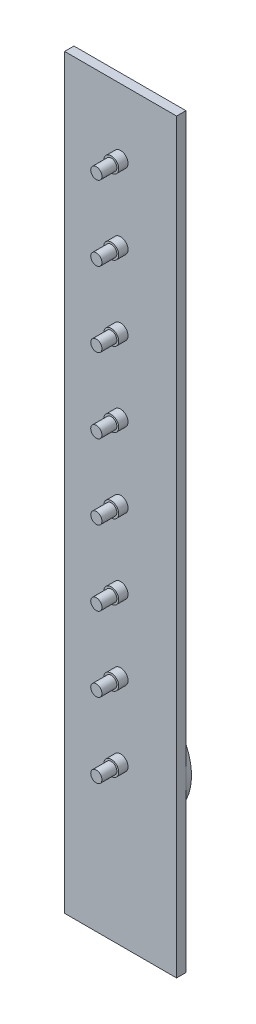
SolidWorks part; units mm, degrees
ref_plane "Спереди" through (0, 0, 0) normal (0, 0, 1) x (1, 0, 0)
ref_plane "Сверху" through (0, 0, 0) normal (0, 1, 0) x (1, 0, 0)
ref_plane "Справа" through (0, 0, 0) normal (1, 0, 0) x (0, 0, -1)
other "Configuration Table"
sketch "Sketch1" plane through (0, 0, 0) normal (0, 0, 1) x (1, 0, 0)
  line L1 (-30, -200) -> (30, -200)
  line L2 (-30, -200) -> (-30, 200)
  line L3 (-30, 200) -> (30, 200)
  line L4 (30, -200) -> (30, 200)
  line L5 (-30, -200) -> (30, 200) construction
  line L6 (-30, 200) -> (30, -200) construction
  point P0 (0, 0)
  dimension "D1" = 60
  dimension "D2" = 400
extrude "Boss-Extrude1" add sketch "Sketch1" along normal blind 5
sketch "Sketch2" plane through (0, 0, 0) normal (0, 0, -1) x (-1, 0, 0)
  line L0 (30, 200) -> (30, -200) construction
  circle A0 centre (0, -110) radius 30
  point P2 (0.2947, -29.9986)
  point P4 (0, 0)
  point P7 (0, -61.8151)
  dimension "D1" = 80
extrude "Boss-Extrude2" add sketch "Sketch2" along normal blind 3
sketch "Sketch3" plane through (0, 0, 5) normal (0, 0, 1) x (1, 0, 0)
  line L0 (0, 186.2824) -> (0, -60.2881) construction
  line L2 (30, 200) -> (-30, 200) construction
  circle A0 centre (0, 165) radius 3
  dimension "D1" = 6
  dimension "D2" = 35
extrude "Boss-Extrude3" add sketch "Sketch3" along normal blind 13
sketch "Sketch4" plane through (0, 0, 5) normal (0, 0, 1) x (1, 0, 0)
  circle A0 centre (0, 165) radius 4
  circle A1 centre (0, 165) radius 3 construction
  dimension "D1" = 1
extrude "Boss-Extrude4" add sketch "Sketch4" along normal blind 5
pattern_linear "LPattern1" count 8 spacing 40 along (0, -1, 0) of "Boss-Extrude4", "Boss-Extrude3"
